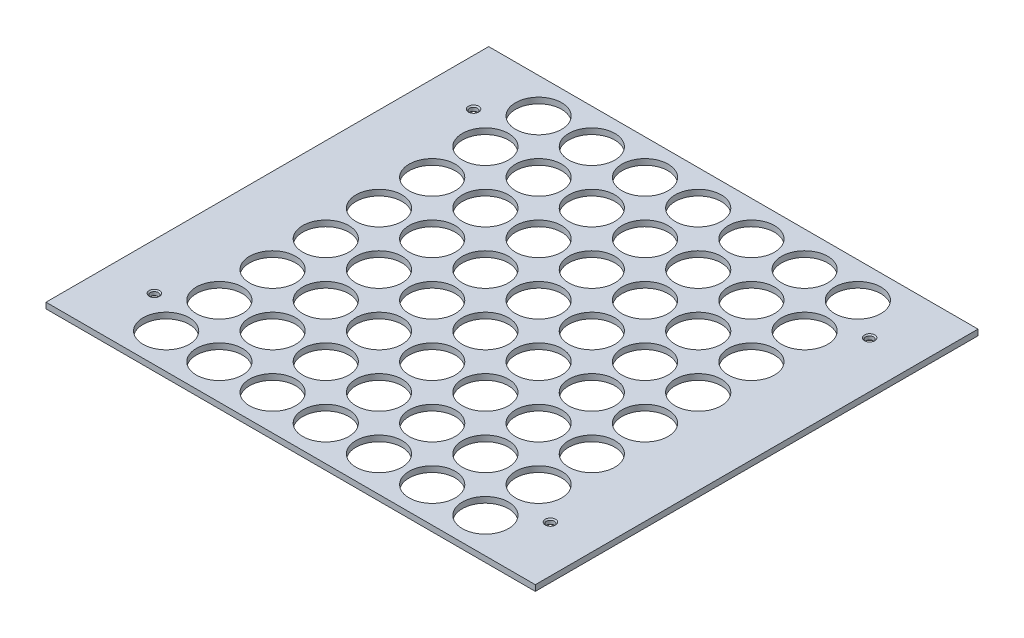
SolidWorks part; units mm, degrees
ref_plane "Front Plane" through (0, 0, 0) normal (0, 0, 1) x (1, 0, 0)
ref_plane "Top Plane" through (0, 0, 0) normal (0, 1, 0) x (1, 0, 0)
ref_plane "Right Plane" through (0, 0, 0) normal (1, 0, 0) x (0, 0, -1)
sketch "Sketch1" plane through (0, 0, 0) normal (0, 1, 0) x (1, 0, 0)
  line L1 (-133.35, 120.65) -> (133.35, 120.65)
  line L2 (-133.35, 120.65) -> (-133.35, -120.65)
  line L3 (-133.35, -120.65) -> (133.35, -120.65)
  line L4 (133.35, 120.65) -> (133.35, -120.65)
  line L5 (-133.35, 120.65) -> (133.35, -120.65) construction
  line L6 (-133.35, -120.65) -> (133.35, 120.65) construction
  circle A0 centre (-87, -101.5) radius 14 construction
  circle A1 centre (-58, -101.5) radius 14 construction
  circle A2 centre (-29, -101.5) radius 14 construction
  circle A3 centre (0, -101.5) radius 14 construction
  circle A4 centre (29, -101.5) radius 14 construction
  circle A5 centre (58, -101.5) radius 14 construction
  circle A6 centre (87, -101.5) radius 14 construction
  circle A7 centre (-58, -72.5) radius 14 construction
  circle A8 centre (-29, -72.5) radius 14 construction
  circle A9 centre (0, -72.5) radius 14 construction
  circle A10 centre (29, -72.5) radius 14 construction
  circle A11 centre (58, -72.5) radius 14 construction
  circle A12 centre (87, -72.5) radius 14 construction
  circle A13 centre (-58, -43.5) radius 14 construction
  circle A14 centre (-29, -43.5) radius 14 construction
  circle A15 centre (0, -43.5) radius 14 construction
  circle A16 centre (29, -43.5) radius 14 construction
  circle A17 centre (58, -43.5) radius 14 construction
  circle A18 centre (87, -43.5) radius 14 construction
  circle A19 centre (-58, -14.5) radius 14 construction
  circle A20 centre (-29, -14.5) radius 14 construction
  circle A21 centre (0, -14.5) radius 14 construction
  circle A22 centre (29, -14.5) radius 14 construction
  circle A23 centre (58, -14.5) radius 14 construction
  circle A24 centre (87, -14.5) radius 14 construction
  circle A25 centre (-58, 14.5) radius 14 construction
  circle A26 centre (-29, 14.5) radius 14 construction
  circle A27 centre (0, 14.5) radius 14 construction
  circle A28 centre (29, 14.5) radius 14 construction
  circle A29 centre (58, 14.5) radius 14 construction
  circle A30 centre (87, 14.5) radius 14 construction
  circle A31 centre (-58, 43.5) radius 14 construction
  circle A32 centre (-29, 43.5) radius 14 construction
  circle A33 centre (0, 43.5) radius 14 construction
  circle A34 centre (29, 43.5) radius 14 construction
  circle A35 centre (58, 43.5) radius 14 construction
  circle A36 centre (87, 43.5) radius 14 construction
  circle A37 centre (-58, 72.5) radius 14 construction
  circle A38 centre (-29, 72.5) radius 14 construction
  circle A39 centre (0, 72.5) radius 14 construction
  circle A40 centre (29, 72.5) radius 14 construction
  circle A41 centre (58, 72.5) radius 14 construction
  circle A42 centre (87, 72.5) radius 14 construction
  circle A43 centre (-58, 101.5) radius 14 construction
  circle A44 centre (-29, 101.5) radius 14 construction
  circle A45 centre (0, 101.5) radius 14 construction
  circle A46 centre (29, 101.5) radius 14 construction
  circle A47 centre (58, 101.5) radius 14 construction
  circle A48 centre (87, 101.5) radius 14 construction
  circle A49 centre (-87, -72.5) radius 14 construction
  circle A50 centre (-87, -43.5) radius 14 construction
  circle A51 centre (-87, -14.5) radius 14 construction
  circle A52 centre (-87, 14.5) radius 14 construction
  circle A53 centre (-87, 43.5) radius 14 construction
  circle A54 centre (-87, 72.5) radius 14 construction
  circle A55 centre (-87, 101.5) radius 14 construction
  circle A56 centre (-87, -101.5) radius 12.573
  circle A57 centre (-58, -101.5) radius 12.573
  circle A58 centre (-29, -101.5) radius 12.573
  circle A59 centre (0, -101.5) radius 12.573
  circle A60 centre (29, -101.5) radius 12.573
  circle A61 centre (58, -101.5) radius 12.573
  circle A62 centre (87, -101.5) radius 12.573
  circle A63 centre (-58, -72.5) radius 12.573
  circle A64 centre (-29, -72.5) radius 12.573
  circle A65 centre (0, -72.5) radius 12.573
  circle A66 centre (29, -72.5) radius 12.573
  circle A67 centre (58, -72.5) radius 12.573
  circle A68 centre (87, -72.5) radius 12.573
  circle A69 centre (-58, -43.5) radius 12.573
  circle A70 centre (-29, -43.5) radius 12.573
  circle A71 centre (0, -43.5) radius 12.573
  circle A72 centre (29, -43.5) radius 12.573
  circle A73 centre (58, -43.5) radius 12.573
  circle A74 centre (87, -43.5) radius 12.573
  circle A75 centre (-58, -14.5) radius 12.573
  circle A76 centre (-29, -14.5) radius 12.573
  circle A77 centre (0, -14.5) radius 12.573
  circle A78 centre (29, -14.5) radius 12.573
  circle A79 centre (58, -14.5) radius 12.573
  circle A80 centre (87, -14.5) radius 12.573
  circle A81 centre (-58, 14.5) radius 12.573
  circle A82 centre (-29, 14.5) radius 12.573
  circle A83 centre (0, 14.5) radius 12.573
  circle A84 centre (29, 14.5) radius 12.573
  circle A85 centre (58, 14.5) radius 12.573
  circle A86 centre (87, 14.5) radius 12.573
  circle A87 centre (-58, 43.5) radius 12.573
  circle A88 centre (-29, 43.5) radius 12.573
  circle A89 centre (0, 43.5) radius 12.573
  circle A90 centre (29, 43.5) radius 12.573
  circle A91 centre (58, 43.5) radius 12.573
  circle A92 centre (87, 43.5) radius 12.573
  circle A93 centre (-58, 72.5) radius 12.573
  circle A94 centre (-29, 72.5) radius 12.573
  circle A95 centre (0, 72.5) radius 12.573
  circle A96 centre (29, 72.5) radius 12.573
  circle A97 centre (58, 72.5) radius 12.573
  circle A98 centre (87, 72.5) radius 12.573
  circle A99 centre (-58, 101.5) radius 12.573
  circle A100 centre (-29, 101.5) radius 12.573
  circle A101 centre (0, 101.5) radius 12.573
  circle A102 centre (29, 101.5) radius 12.573
  circle A103 centre (58, 101.5) radius 12.573
  circle A104 centre (87, 101.5) radius 12.573
  circle A105 centre (-87, -72.5) radius 12.573
  circle A106 centre (-87, -43.5) radius 12.573
  circle A107 centre (-87, -14.5) radius 12.573
  circle A108 centre (-87, 14.5) radius 12.573
  circle A109 centre (-87, 43.5) radius 12.573
  circle A110 centre (-87, 72.5) radius 12.573
  circle A111 centre (-87, 101.5) radius 12.573
  point P0 (0, 0)
  dimension "D1" = 28
  dimension "D10" = 25.146
  dimension "D4" = 87
  dimension "D5" = 101.5
  dimension "D6" = 241.3
  dimension "D7" = 266.7
  dimension "D8" = 29
  dimension "D9" = 29
  dimension "D13" = 29
  dimension "D14" = 29
  dimension "D2" = 7
  dimension "D3" = 8
  dimension "D11" = 7
  dimension "D12" = 8
extrude "Boss-Extrude1" add sketch "Sketch1" along normal blind 3.175
sketch "Sketch2" plane through (0, 3.175, 0) normal (0, 1, 0) x (1, 0, 0)
  line L0 (-156.2281, 0) -> (176.9374, 0) construction
  line L1 (-139.5153, 86.995) -> (160.9513, 86.995) construction
  line L2 (-149.6883, -86.995) -> (160.9513, -86.995) construction
  line L3 (-107.95, 126.7991) -> (-107.95, -136.9721) construction
  line L4 (107.95, 126.7991) -> (107.95, -132.6122) construction
  dimension "D1" = 107.95
  dimension "D2" = 107.95
  dimension "D3" = 86.995
  dimension "D4" = 86.995
hole_wizard "#6 Clearance Hole1" positions "Sketch3" profile "Sketch4" hole size "#6" standard "ANSI Inch" end condition through all
sketch "Sketch3" plane through (0, 3.175, 0) normal (0, 1, 0) x (1, 0, 0)
  line L0 (-139.5153, 86.995) -> (160.9513, 86.995) construction
  line L1 (-149.6883, -86.995) -> (160.9513, -86.995) construction
  line L2 (107.95, 126.7991) -> (107.95, -132.6122) construction
  line L3 (-107.95, 126.7991) -> (-107.95, -136.9721) construction
  point P0 (-107.95, 86.995)
  point P4 (107.95, 86.995)
  point P6 (107.95, -86.995)
  point P12 (-107.95, -86.995)
sketch "Sketch4" plane through (-107.95, 3.175, -86.995) normal (1, 0, 0) x (0, 0, 1)
  line L0 (0, 0) -> (0, 3.175)
  line L1 (0, 3.175) -> (2.7876, 3.175)
  line L2 (2.1526, 2.54) -> (2.1526, 0.635)
  line L3 (2.1526, 0.635) -> (2.7876, 0)
  line L5 (2.7876, 0) -> (0, 0)
  line L6 (-2.1526, 0.635) -> (-2.7876, 0) construction
  line L7 (2.7876, 3.175) -> (2.1526, 2.54)
  line L8 (-2.7877, 3.175) -> (-2.1527, 2.54) construction
  line L11 (0, -6.35) -> (0, 107.95) construction
  dimension "Thru Hole Dia." = 4.3053
  dimension "Thru Hole Depth" = 3.175
  dimension "Near C'Sink Dia." = 5.5753
  dimension "Near C'Sink Angle" = 90
  dimension "Far C'Sink Dia." = 5.5753
  dimension "Far C'Sink Angle" = 90
